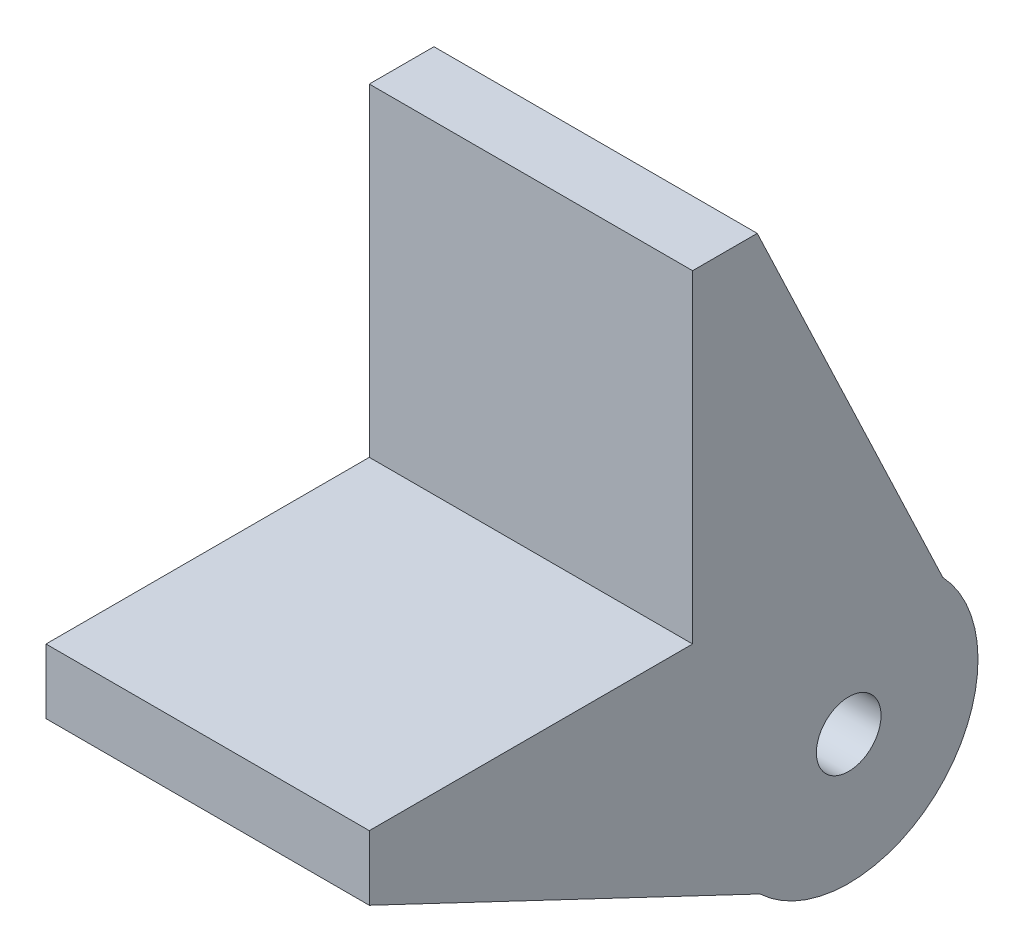
SolidWorks part; units mm, degrees
ref_plane "前视基准面" through (0, 0, 0) normal (0, 0, 1) x (1, 0, 0)
ref_plane "上视基准面" through (0, 0, 0) normal (0, 1, 0) x (1, 0, 0)
ref_plane "右视基准面" through (0, 0, 0) normal (1, 0, 0) x (0, 0, -1)
sketch "草图1" plane through (0, 0, 0) normal (0, 0, 1) x (1, 0, 0)
  line L1 (0, 0) -> (10, 0)
  line L2 (0, 0) -> (0, 10)
  line L3 (0, 10) -> (10, 10)
  line L4 (10, 0) -> (10, 10)
extrude "凸台-拉伸1" add sketch "草图1" along normal blind 2
sketch "草图2" plane through (0, 0, 0) normal (0, -1, 0) x (1, 0, 0)
  line L0 (10, 2) -> (10, 0) construction
  line L1 (10, 0) -> (0, 0)
  line L2 (10, 0) -> (10, 12)
  line L3 (10, 12) -> (0, 12)
  line L4 (0, 0) -> (0, 12)
  line L5 (0, 0) -> (10, 0) construction
extrude "凸台-拉伸2" add sketch "草图2" along normal blind 2
sketch "草图3" plane through (10, 0, 0) normal (1, 0, 0) x (0, 0, -1)
  line L0 (-2, 0) -> (0, -2)
  line L1 (0, -2) -> (2.8284, -4.8284)
  line L2 (0, 4) -> (5.7383, -2.0838)
  line L3 (0, -2) -> (0, 10) construction
  line L4 (-6, -2) -> (0.0838, -7.7383)
  line L5 (0, -2) -> (-12, -2) construction
  line L6 (-12, -2) -> (0.0838, -7.7383)
  line L7 (0, 10) -> (5.7383, -2.0838)
  circle A0 centre (2.8284, -4.8284) radius 4
extrude "凸台-拉伸4" add sketch "草图3" against normal blind 2
sketch "草图4" plane through (0, 0, 0) normal (-1, 0, 0) x (0, 0, 1)
  line L0 (2, 0) -> (0, -2)
  line L1 (0, -2) -> (-2.8284, -4.8284)
  line L2 (0, 4) -> (-5.7383, -2.0838)
  line L3 (0, 10) -> (0, -2) construction
  line L4 (6, -2) -> (-0.0838, -7.7383)
  line L6 (12, -2) -> (0, -2) construction
  line L7 (-0.0838, -7.7383) -> (12, -2)
  line L8 (0, 10) -> (-5.7383, -2.0838)
  circle A0 centre (-2.8284, -4.8284) radius 4
extrude "凸台-拉伸5" add sketch "草图4" against normal blind 2
sketch "草图5" plane through (10, 0, 0) normal (1, 0, 0) x (0, 0, -1)
  line L0 (-2, 0) -> (2.8284, -4.8284)
  circle A0 centre (2.8284, -4.8284) radius 1
extrude "切除-拉伸1" cut sketch "草图5" against normal blind 10
